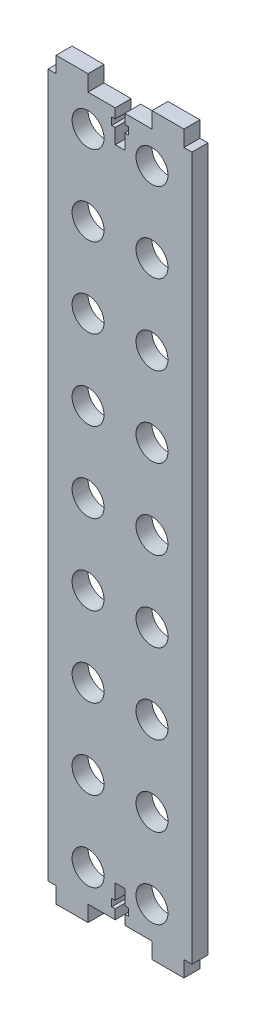
SolidWorks part; units mm, degrees
ref_plane "Front Plane" through (0, 0, 0) normal (0, 0, 1) x (1, 0, 0)
ref_plane "Top Plane" through (0, 0, 0) normal (0, 1, 0) x (1, 0, 0)
ref_plane "Right Plane" through (0, 0, 0) normal (1, 0, 0) x (0, 0, -1)
sketch "Sketch1" plane through (0, 0, 0) normal (0, 0, 1) x (1, 0, 0)
  line L0 (-56.8004, 0) -> (-54.3004, 0)
  line L1 (-54.3004, 0) -> (-54.3004, -5)
  line L2 (-54.3004, -5) -> (-44.3004, -5)
  line L3 (-44.3004, -5) -> (-44.3004, 0)
  line L4 (-44.3004, 0) -> (-35.8004, 0)
  line L5 (-56.8004, 0) -> (-56.8004, 220)
  line L6 (-56.8004, 220) -> (-54.3004, 220)
  line L7 (-54.3004, 225) -> (-44.3004, 225)
  line L8 (-44.3004, 225) -> (-44.3004, 220)
  line L9 (-44.3004, 220) -> (-35.8004, 220)
  line L10 (-54.3004, 225) -> (-54.3004, 220)
  line L11 (-14.3004, 225) -> (-14.3004, 220)
  line L12 (-32.8004, 220) -> (-24.3004, 220)
  line L13 (-24.3004, 225) -> (-24.3004, 220)
  line L14 (-14.3004, 225) -> (-24.3004, 225)
  line L15 (-11.8004, 220) -> (-14.3004, 220)
  line L16 (-11.8004, -0.0207) -> (-11.8004, 220)
  line L21 (-32.8004, 0) -> (-24.3004, 0)
  line L22 (-32.8004, 220) -> (-35.8004, 220) construction
  line L23 (-35.8004, 220) -> (-35.8004, 217)
  line L24 (-35.8004, 214.7) -> (-36.9004, 214.7)
  line L25 (-31.7004, 217) -> (-31.7004, 214.7)
  line L26 (-36.9004, 217) -> (-35.8004, 217)
  line L27 (-35.8004, 214.7) -> (-35.8004, 210)
  line L28 (-35.8004, 210) -> (-32.8004, 210)
  line L29 (-32.8004, 210) -> (-32.8004, 214.7)
  line L30 (-32.8004, 217) -> (-31.7004, 217)
  line L31 (-36.9004, 214.7) -> (-36.9004, 217)
  line L32 (-31.7004, 214.7) -> (-32.8004, 214.7)
  line L33 (-32.8004, 217) -> (-32.8004, 220)
  line L34 (-34.3004, 210) -> (-34.3004, 220) construction
  line L35 (-35.8004, 0) -> (-32.8004, 0) construction
  line L36 (-32.8004, 0) -> (-32.8004, 3)
  line L37 (-32.8004, 5.3) -> (-31.7004, 5.3)
  line L38 (-36.9004, 3) -> (-36.9004, 5.3)
  line L39 (-31.7004, 3) -> (-32.8004, 3)
  line L40 (-32.8004, 5.3) -> (-32.8004, 10)
  line L41 (-32.8004, 10) -> (-35.8004, 10)
  line L42 (-35.8004, 10) -> (-35.8004, 5.3)
  line L43 (-35.8004, 3) -> (-36.9004, 3)
  line L44 (-31.7004, 5.3) -> (-31.7004, 3)
  line L45 (-36.9004, 5.3) -> (-35.8004, 5.3)
  line L46 (-35.8004, 3) -> (-35.8004, 0)
  line L47 (-34.3004, 10) -> (-34.3004, 0) construction
  line L48 (-44.3004, 236.532) -> (-44.3004, -42.8879) construction
  line L49 (-24.3004, -42.8879) -> (-24.3004, 236.532) construction
  line L50 (-24.3004, 0) -> (-24.3004, -5)
  line L51 (-24.3004, -5) -> (-14.3004, -5)
  line L52 (-14.3004, -5) -> (-14.3004, -0.0207)
  line L53 (-14.3004, -0.0207) -> (-11.8004, -0.0207)
  circle A0 centre (-44.3004, 210) radius 5
  circle A1 centre (-24.3004, 210) radius 5
  circle A2 centre (-24.3004, 185) radius 5
  circle A3 centre (-24.3004, 160) radius 5
  circle A4 centre (-24.3004, 135) radius 5
  circle A5 centre (-24.3004, 110) radius 5
  circle A6 centre (-24.3004, 85) radius 5
  circle A7 centre (-24.3004, 60) radius 5
  circle A8 centre (-24.3004, 35) radius 5
  circle A9 centre (-24.3004, 10) radius 5
  circle A10 centre (-44.3004, 185) radius 5
  circle A11 centre (-44.3004, 160) radius 5
  circle A12 centre (-44.3004, 135) radius 5
  circle A13 centre (-44.3004, 110) radius 5
  circle A14 centre (-44.3004, 85) radius 5
  circle A15 centre (-44.3004, 60) radius 5
  circle A16 centre (-44.3004, 35) radius 5
  circle A17 centre (-44.3004, 10) radius 5
  dimension "D21" = 15
  dimension "D3" = 2.5
  dimension "D1" = 5
  dimension "D2" = 10
  dimension "D4" = 45
  dimension "D5" = 230
  dimension "D6" = 5
  dimension "D7" = 5.2
  dimension "D8" = 3
  dimension "D9" = 2.3
  dimension "D10" = 3
  dimension "D11" = 10
  dimension "D12" = 5
  dimension "D13" = 10
  dimension "D14" = 5.2
  dimension "D15" = 3
  dimension "D16" = 2.3
  dimension "D17" = 3
  dimension "D18" = 10
  dimension "D19" = 12.5
  dimension "D20" = 12.5
  dimension "D24" = 2.5
  dimension "D25" = 5
  dimension "D26" = 20
  dimension "D27" = 10
  dimension "D28" = 2.5
  dimension "D29" = 22.5
  dimension "D30" = 10
  dimension "D22" = 2
  dimension "D23" = 9
extrude "Boss-Extrude1" add sketch "Sketch1" along normal blind 5
